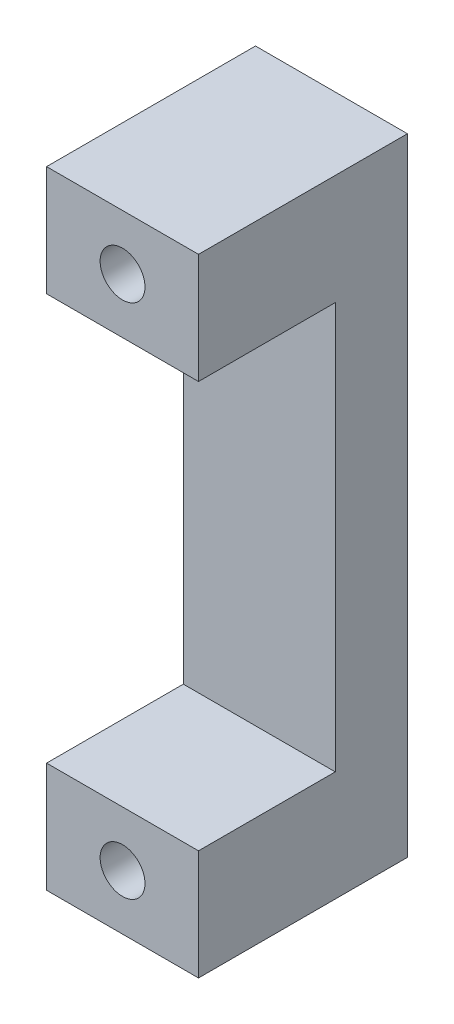
SolidWorks part; units mm, degrees
ref_plane "Front Plane" through (0, 0, 0) normal (0, 0, 1) x (1, 0, 0)
ref_plane "Top Plane" through (0, 0, 0) normal (0, 1, 0) x (1, 0, 0)
ref_plane "Right Plane" through (0, 0, 0) normal (1, 0, 0) x (0, 0, -1)
sketch "Sketch1" plane through (0, 0, 0) normal (0, 0, 1) x (1, 0, 0)
  line L1 (0, 0) -> (10.16, 0)
  line L2 (0, 0) -> (0, 41.91)
  line L3 (0, 41.91) -> (10.16, 41.91)
  line L4 (10.16, 0) -> (10.16, 41.91)
  dimension "D1" = 41.91
  dimension "D2" = 10.16
extrude "Boss-Extrude1" add sketch "Sketch1" along normal blind 13.97
ref_plane "Plane1" through (0, 20.955, 0) normal (0, 1, 0) x (1, 0, 0)
ref_plane "Plane2" through (5.08, 0, 0) normal (1, 0, 0) x (0, 0, -1)
sketch "Sketch2" plane through (0, 0, 13.97) normal (0, 0, 1) x (1, 0, 0)
  line L0 (0, 41.91) -> (0, 0) construction
  line L1 (0, 34.544) -> (10.16, 34.544)
  line L2 (0, 34.544) -> (0, 7.366)
  line L3 (0, 7.366) -> (10.16, 7.366)
  line L4 (10.16, 34.544) -> (10.16, 7.366)
  line L5 (10.16, 0) -> (10.16, 41.91) construction
  line L6 (5.588, 20.955) -> (-5.588, 20.955) construction
  point P10 (10.16, 20.955)
  dimension "D1" = 27.178
extrude "Cut-Extrude1" cut sketch "Sketch2" against normal blind 9.144
ref_plane "Plane3" through (0, 38.227, 0) normal (0, 1, 0) x (1, 0, 0)
ref_plane "Plane4" through (0, 3.683, 0) normal (0, 1, 0) x (1, 0, 0)
hole_wizard "Ø3.0mm Dowel Hole1" positions "Sketch3" profile "Sketch4" hole size "Ø3.0" standard "ANSI Metric" end condition up to next
sketch "Sketch3" plane through (0, 0, 13.97) normal (0, 0, 1) x (1, 0, 0)
  line L3 (5.08, -7.6835) -> (5.08, 7.6835) construction
  line L4 (5.588, 3.683) -> (-5.588, 3.683) construction
  line L5 (5.588, 38.227) -> (-5.588, 38.227) construction
  point P0 (5.08, 3.683)
  point P2 (5.08, 38.227)
  point P11 (0, 0)
  point P12 (0, 0)
  point P15 (0, 0)
  point P16 (0, 0)
  point P19 (0, 0)
sketch "Sketch4" plane through (5.08, 3.683, 13.97) normal (1, 0, 0) x (0, -1, 0)
  line L0 (0, 0) -> (0, 13.97)
  line L1 (0, 13.97) -> (1.5, 13.97)
  line L2 (1.5, 13.97) -> (1.5, 0)
  line L5 (1.5, 0) -> (0, 0)
  line L11 (0, -6.35) -> (0, 107.95) construction
  dimension "Thru Hole Dia." = 3
  dimension "Thru Hole Depth" = 13.97
